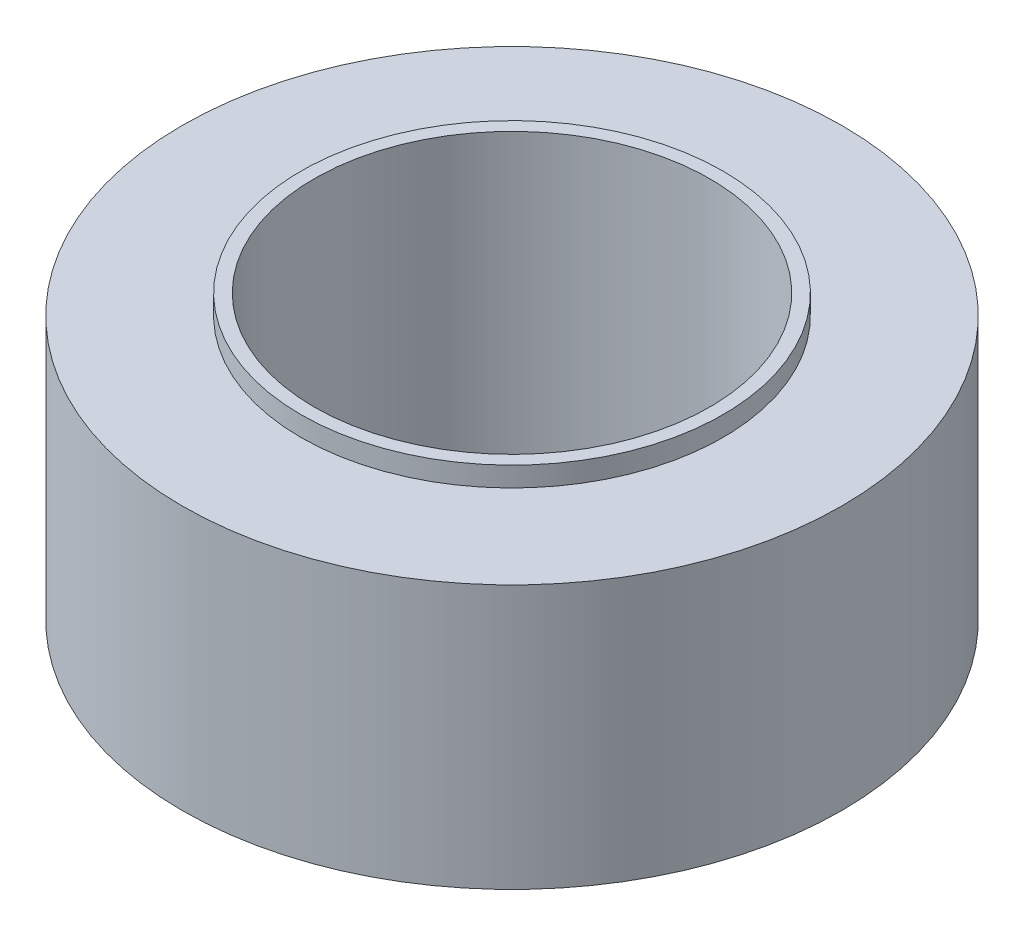
SolidWorks part; units mm, degrees
ref_plane "Front Plane" through (0, 0, 0) normal (0, 0, 1) x (1, 0, 0)
ref_plane "Top Plane" through (0, 0, 0) normal (0, 1, 0) x (1, 0, 0)
ref_plane "Right Plane" through (0, 0, 0) normal (1, 0, 0) x (0, 0, -1)
sketch "Sketch1" plane through (0, 0, 0) normal (0, 1, 0) x (1, 0, 0)
  line L0 (-500, 0) -> (24500, 0) construction
  line L1 (0, -500) -> (0, 24500) construction
  circle A0 centre (0, 0) radius 12.5
  circle A1 centre (0, 0) radius 7.5
  dimension "D1" = 25
  dimension "D2" = 15
extrude "Boss-Extrude2" add sketch "Sketch1" against normal blind 10
sketch "Sketch2" plane through (0, 0, 0) normal (0, 1, 0) x (1, 0, 0)
  circle A0 centre (0, 0) radius 8
  circle A1 centre (0, 0) radius 7.5
extrude "Boss-Extrude3" add sketch "Sketch2" along normal blind 0.75
